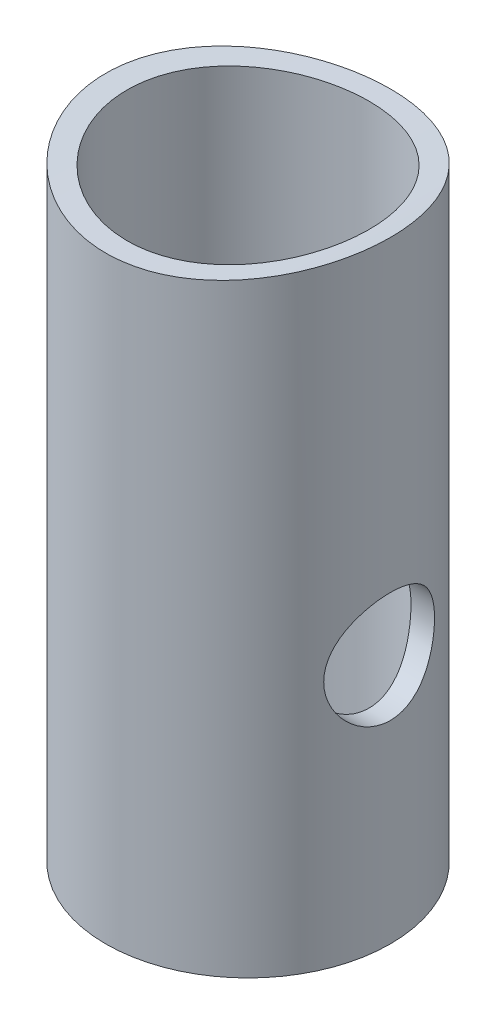
SolidWorks part; units mm, degrees
ref_plane "Front Plane" through (0, 0, 0) normal (0, 0, 1) x (1, 0, 0)
ref_plane "Top Plane" through (0, 0, 0) normal (0, 1, 0) x (1, 0, 0)
ref_plane "Right Plane" through (0, 0, 0) normal (1, 0, 0) x (0, 0, -1)
sketch "Sketch1" plane through (0, 0, 0) normal (0, 1, 0) x (1, 0, 0)
  circle A0 centre (0, 0) radius 57.15
  circle A1 centre (0, 0) radius 48.59
  dimension "D1" = 114.3
  dimension "D2" = 8.56
extrude "Boss-Extrude1" add sketch "Sketch1" along normal blind 245.75
sketch "Sketch2" plane through (0, 0, 0) normal (0, 0, 1) x (1, 0, 0)
  line L1 (57.15, 245.75) -> (-57.15, 245.75) construction
  line L2 (57.15, 245.75) -> (-57.15, 245.75)
  arc A0 (-57.15, 245.75) -> (57.15, 245.75) centre (0, 543.5615) ccw
  dimension "D1" = 606.4909
extrude "Cut-Extrude1" cut sketch "Sketch2" against normal through all both and the other way through all
sketch "Sketch3" plane through (0, 0, 0) normal (1, 0, 0) x (0, 0, -1)
  circle A0 centre (0, 100) radius 22.25
  point P2 (0, 0)
  point P4 (0, 0)
  dimension "D1" = 44.5
  dimension "D2" = 100
extrude "Cut-Extrude2" cut sketch "Sketch3" along normal blind 111
